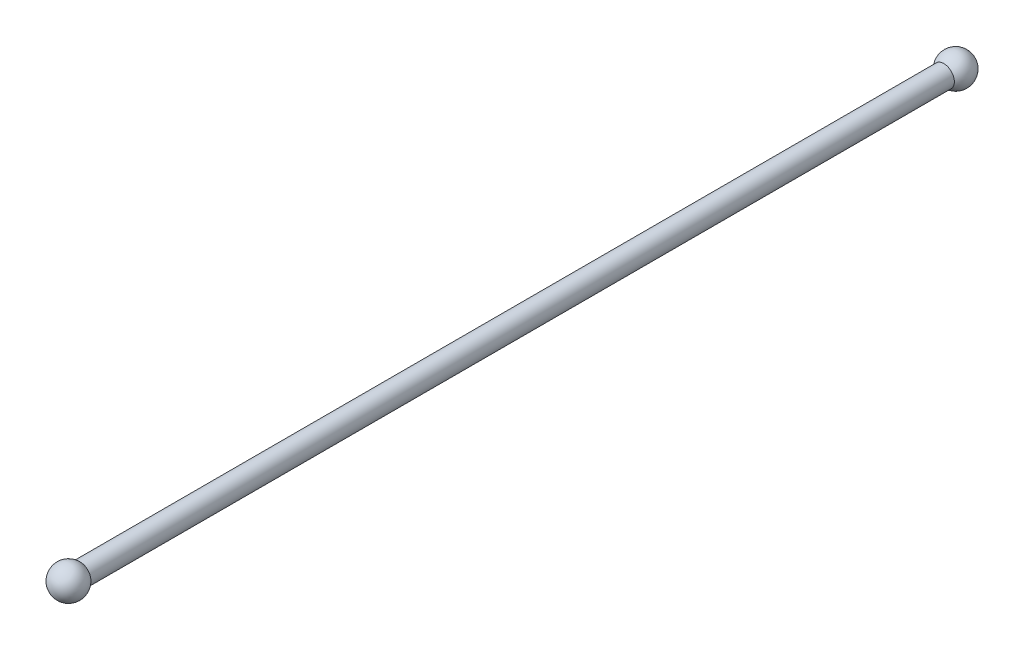
SolidWorks part; units mm, degrees
ref_plane "Front Plane" through (0, 0, 0) normal (0, 0, 1) x (1, 0, 0)
ref_plane "Top Plane" through (0, 0, 0) normal (0, 1, 0) x (1, 0, 0)
ref_plane "Right Plane" through (0, 0, 0) normal (1, 0, 0) x (0, 0, -1)
sketch "Sketch3" plane through (0, 0, 0) normal (0, 1, 0) x (1, 0, 0)
  line L0 (0, 0) -> (0, 335) construction
  line L1 (-4, 330.5279) -> (-4, 4.4721)
  line L2 (0, 341) -> (0, -6)
  arc A0 (-4, 4.4721) -> (0, -6) centre (0, 0) ccw
  arc A1 (0, 341) -> (-4, 330.5279) centre (0, 335) ccw
  dimension "D2" = 6
  dimension "D1" = 335
  dimension "D3" = 4
revolve "Revolve1" add sketch "Sketch3" angle 360 about L0
